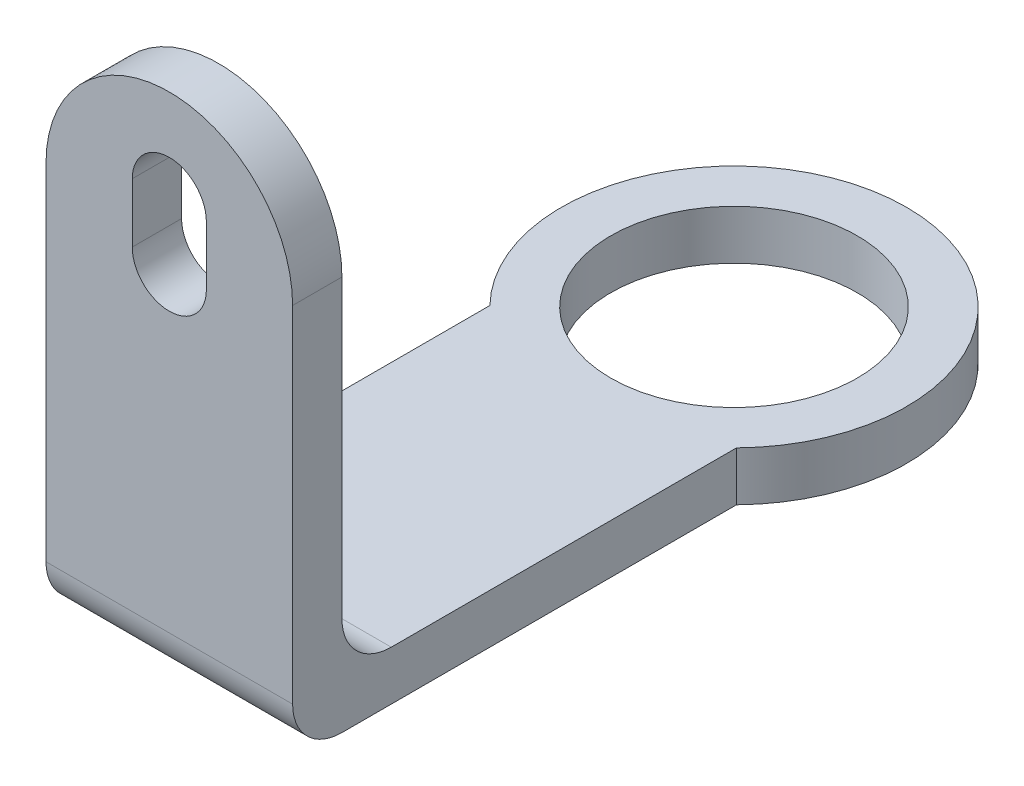
SolidWorks part; units mm, degrees
material "Латунь"
ref_plane "Спереди" through (0, 0, 0) normal (0, 0, 1) x (1, 0, 0)
ref_plane "Сверху" through (0, 0, 0) normal (0, 1, 0) x (1, 0, 0)
ref_plane "Справа" through (0, 0, 0) normal (1, 0, 0) x (0, 0, -1)
sketch "Эскиз1" plane through (0, 0, 0) normal (0, 1, 0) x (1, 0, 0)
  line L0 (-2.5, -2.4495) -> (-2.5, -10.4495)
  line L1 (2.5, -2.4495) -> (2.5, -10.4495)
  line L2 (2.5, -10.4495) -> (-2.5, -10.4495)
  circle A0 centre (0, 0) radius 2.5
  arc A1 (2.5, -2.4495) -> (-2.5, -2.4495) centre (0, 0) ccw
  dimension "D1" = 5
  dimension "D2" = 7
  dimension "D3" = 8
extrude "Бобышка-Вытянуть2" add sketch "Эскиз1" along normal blind 1
sketch "Эскиз3" plane through (0, 0, 10.4495) normal (0, 0, 1) x (1, 0, 0)
  line L0 (0, 7.4) -> (0, 8.6) construction
  line L1 (2.5, 0) -> (-2.5, 0)
  line L2 (2.5, 0) -> (2.5, 8)
  line L4 (-2.5, 0) -> (-2.5, 8)
  line L5 (-0.7512, 7.4) -> (-0.7512, 8.6)
  line L6 (0.7512, 7.4) -> (0.7512, 8.6)
  arc A0 (2.5, 8) -> (-2.5, 8) centre (0, 8) ccw
  arc A1 (-0.7512, 7.4) -> (0.7512, 7.4) centre (0, 7.4) ccw
  arc A2 (0.7512, 8.6) -> (-0.7512, 8.6) centre (0, 8.6) ccw
  point P8 (0, 8)
  dimension "D4" = 2.5
  dimension "D5" = 0.7512
  dimension "D1" = 8
  dimension "D2" = 5
  dimension "D3" = 1.2
extrude "Бобышка-Вытянуть3" add sketch "Эскиз3" along normal blind 1
fillet "Скругление1" radius 1 2 edges at (0, 1, 10.4495) (0, 0, 11.4495)
